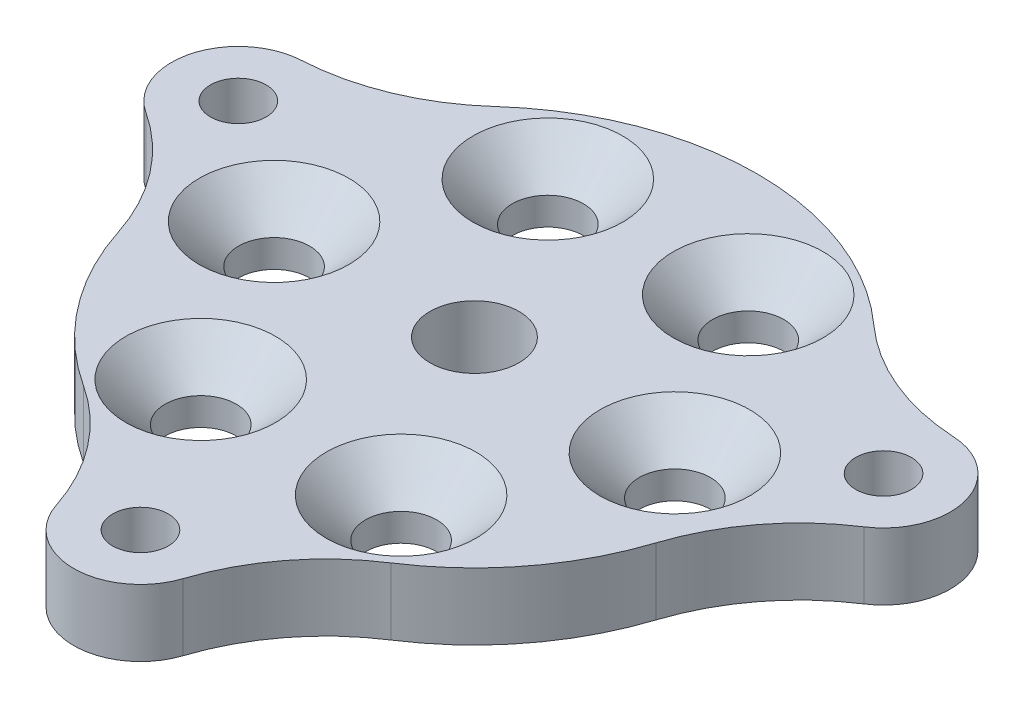
SolidWorks part; units mm, degrees
material "6061-T6 (SS)"
ref_plane "Front Plane" through (0, 0, 0) normal (0, 0, 1) x (1, 0, 0)
ref_plane "Top Plane" through (0, 0, 0) normal (0, 1, 0) x (1, 0, 0)
ref_plane "Right Plane" through (0, 0, 0) normal (1, 0, 0) x (0, 0, -1)
sketch "Sketch1" plane through (0, 0, 0) normal (0, 1, 0) x (1, 0, 0)
  circle A0 centre (0, 0) radius 12.7
  circle A1 centre (0, 0) radius 2
  dimension "D1" = 4
  dimension "D2" = 25.4
extrude "Boss-Extrude1" add sketch "Sketch1" along normal blind 3
hole_wizard "CSK for M3 SFHCS1" positions "Sketch2" profile "Sketch3" countersink size "M3" standard "ANSI Metric" end condition through all
sketch "Sketch2" plane through (0, 3, 0) normal (0, 1, 0) x (1, 0, 0)
  circle A3 centre (0, 0) radius 9 construction
  point P65 (-4.5, 7.7942)
  point P72 (4.5, 7.7942)
  point P73 (9, 0)
  point P74 (4.5, -7.7942)
  point P75 (-4.5, -7.7942)
  point P76 (-9, 0)
  point P78 (-8.9022, -1.3233)
  point P79 (-3.3842, -8.3395)
  point P80 (0, 0)
  dimension "D1" = 18
  dimension "D2" = 6
sketch "Sketch3" plane through (-9, 3, 0) normal (1, 0, 0) x (0, 0, 1)
  line L0 (0, 0) -> (0, 3)
  line L1 (0, 3) -> (1.6, 3)
  line L2 (1.6, 3) -> (1.6, 1.76)
  line L3 (1.6, 1.76) -> (3.36, 0)
  line L5 (3.36, 0) -> (0, 0)
  line L6 (-1.6, 1.76) -> (-3.36, 0) construction
  line L11 (0, -6.35) -> (0, 107.95) construction
  dimension "Thru Hole Dia." = 3.2
  dimension "Thru Hole Depth" = 3
  dimension "Near C'Sink Dia." = 6.72
  dimension "Near C'Sink Angle" = 90
sketch "Sketch6" plane through (0, 3, 0) normal (0, 1, 0) x (1, 0, 0)
  line L0 (0, 0) -> (0, -15) construction
  line L1 (0, 0) -> (14.4889, 3.8823) construction
  circle A0 centre (14.4889, 3.8823) radius 3
  circle A1 centre (0, -15) radius 3
  circle A2 centre (-14.4889, 3.8823) radius 3
  dimension "D3" = 6
  dimension "D1" = 75
  dimension "D2" = 15
extrude "Boss-Extrude2" add sketch "Sketch6" against normal up to surface (3 mm away) up to face at (-4.5, 0, -6.1942)
fillet "Fillet1" radius 10 6 edges at (-11.6902, 1.5, -4.9628) (-12.6054, 1.5, -1.5472) (12.6054, 1.5, -1.5472) (11.6902, 1.5, -4.9628) (-1.768, 1.5, 12.5763) (1.768, 1.5, 12.5763)
hole_wizard "Tap Drill for M3x0.5 Tap1" positions "Sketch7" profile "Sketch8" hole size "M3x0.5" standard "ANSI Metric" end condition through all
sketch "Sketch7" plane through (0, 3, 0) normal (0, 1, 0) x (1, 0, 0)
  point P0 (-14.4889, 3.8823)
  point P3 (14.4889, 3.8823)
  point P6 (0, -15)
sketch "Sketch8" plane through (-14.4889, 3, -3.8823) normal (1, 0, 0) x (0, 0, 1)
  line L0 (0, 0) -> (0, 3)
  line L1 (0, 3) -> (1.25, 3)
  line L2 (1.25, 3) -> (1.25, 0)
  line L5 (1.25, 0) -> (0, 0)
  line L11 (0, -6.35) -> (0, 107.95) construction
  dimension "Thru Hole Dia." = 2.5
  dimension "Thru Hole Depth" = 3
